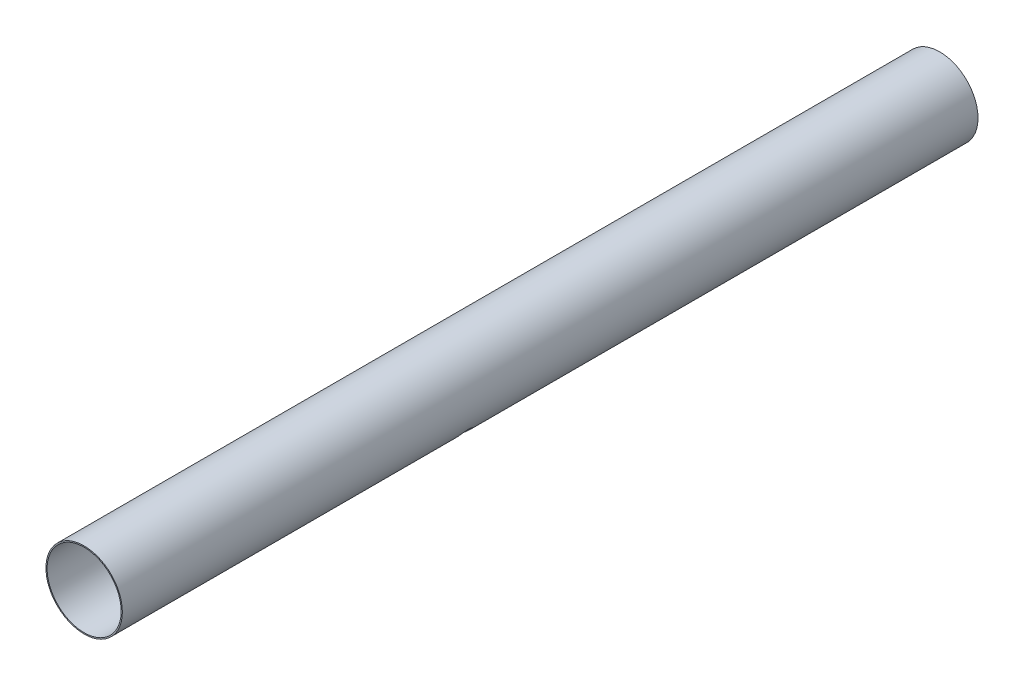
SolidWorks part; units mm, degrees
material "E-Glass Fiber"
ref_plane "Front" through (0, 0, 0) normal (0, 0, 1) x (1, 0, 0)
ref_plane "Top" through (0, 0, 0) normal (0, 1, 0) x (1, 0, 0)
ref_plane "Right" through (0, 0, 0) normal (1, 0, 0) x (0, 0, -1)
sketch "Sketch1" plane through (0, 0, 0) normal (0, 0, 1) x (1, 0, 0)
  circle A0 centre (0, 0) radius 78.6
  circle A1 centre (0, 0) radius 76.2
  dimension "D1" = 157.2
  dimension "D2" = 152.4
  dimension "D3" = 2.4
extrude "Boss-Extrude1" add sketch "Sketch1" along normal blind 1760
sketch "Sketch4" plane through (0, 0, 0) normal (0, 0, 1) x (1, 0, 0)
  line L0 (0, 0) -> (25.0476, -25.0476) construction
  line L1 (0, 0) -> (0, -24.8691) construction
  dimension "D1" = 45
ref_plane "Plane1" through (0, 0, 0) normal (0.7071, -0.7071, 0) x (0, 0, -1)
sketch "Sketch5" plane through (0, 0, 0) normal (0.7071, -0.7071, 0) x (0, 0, -1)
  line L0 (0, -78.6) -> (0, 78.6) construction
  circle A0 centre (-1034.89, 0) radius 15
  dimension "D1" = 30
  dimension "D2" = 1034.89
extrude "Cut-Extrude2" cut sketch "Sketch5" along normal through all
